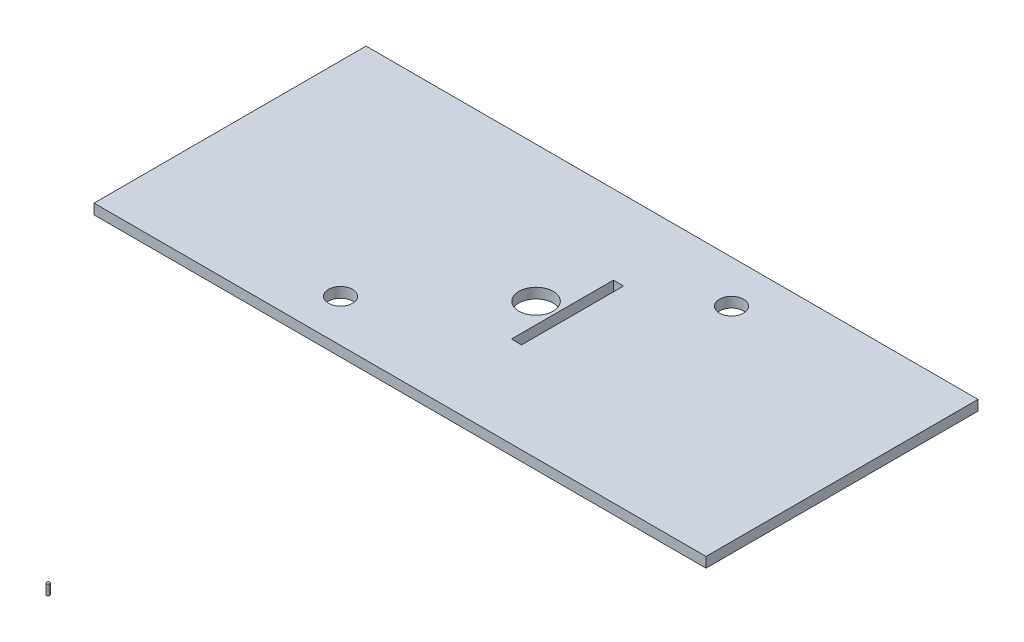
SolidWorks part; units mm, degrees
ref_plane "Plano frontal" through (0, 0, 0) normal (0, 0, 1) x (1, 0, 0)
ref_plane "Plano superior" through (0, 0, 0) normal (0, 1, 0) x (1, 0, 0)
ref_plane "Plano direito" through (0, 0, 0) normal (1, 0, 0) x (0, 0, -1)
sketch "Esboço1" plane through (0, 0, 0) normal (0, 1, 0) x (1, 0, 0)
  line L1 (90, -40) -> (-90, -40)
  line L2 (90, -40) -> (90, 40)
  line L3 (90, 40) -> (-90, 40)
  line L4 (-90, -40) -> (-90, 40)
  line L5 (90, -40) -> (-90, 40) construction
  line L6 (90, 40) -> (-90, -40) construction
  circle A0 centre (0, -143.5) radius 0.45
  circle A1 centre (0, 0) radius 5.05
  point P0 (0, 0)
  point P6 (0, 0)
  dimension "D3" = 10.1
  dimension "D1" = 80
  dimension "D2" = 180
extrude "Ressalto-extrusão1" add sketch "Esboço1" along normal blind 3
sketch "Esboço3" plane through (0, 3, 0) normal (0, 1, 0) x (1, 0, 0)
  circle A0 centre (30, 27.5) radius 3.55
  circle A1 centre (-30, -27.5) radius 3.55
  dimension "D1" = 7.1
  dimension "D2" = 7.1
  dimension "D3" = 30
  dimension "D4" = 30
  dimension "D5" = 27.5
  dimension "D6" = 27.5
extrude "Corte-extrusão2" cut sketch "Esboço3" against normal blind 100
sketch "Esboço4" plane through (0, 3, 0) normal (0, 1, 0) x (1, 0, 0)
  line L0 (-90, -40) -> (90, -40) construction
  line L1 (6, 16.7481) -> (9, 16.7481)
  line L2 (6, 16.7481) -> (6, -13.2519)
  line L3 (6, -13.2519) -> (9, -13.2519)
  line L4 (9, 16.7481) -> (9, -13.2519)
  line L5 (6, 16.7481) -> (9, -13.2519) construction
  line L6 (6, -13.2519) -> (9, 16.7481) construction
  point P0 (7.5, 1.7481)
  dimension "D1" = 3
  dimension "D2" = 30
  dimension "D3" = 7.5
  dimension "D4" = 41.7481
extrude "Corte-extrusão3" cut sketch "Esboço4" against normal blind 10
